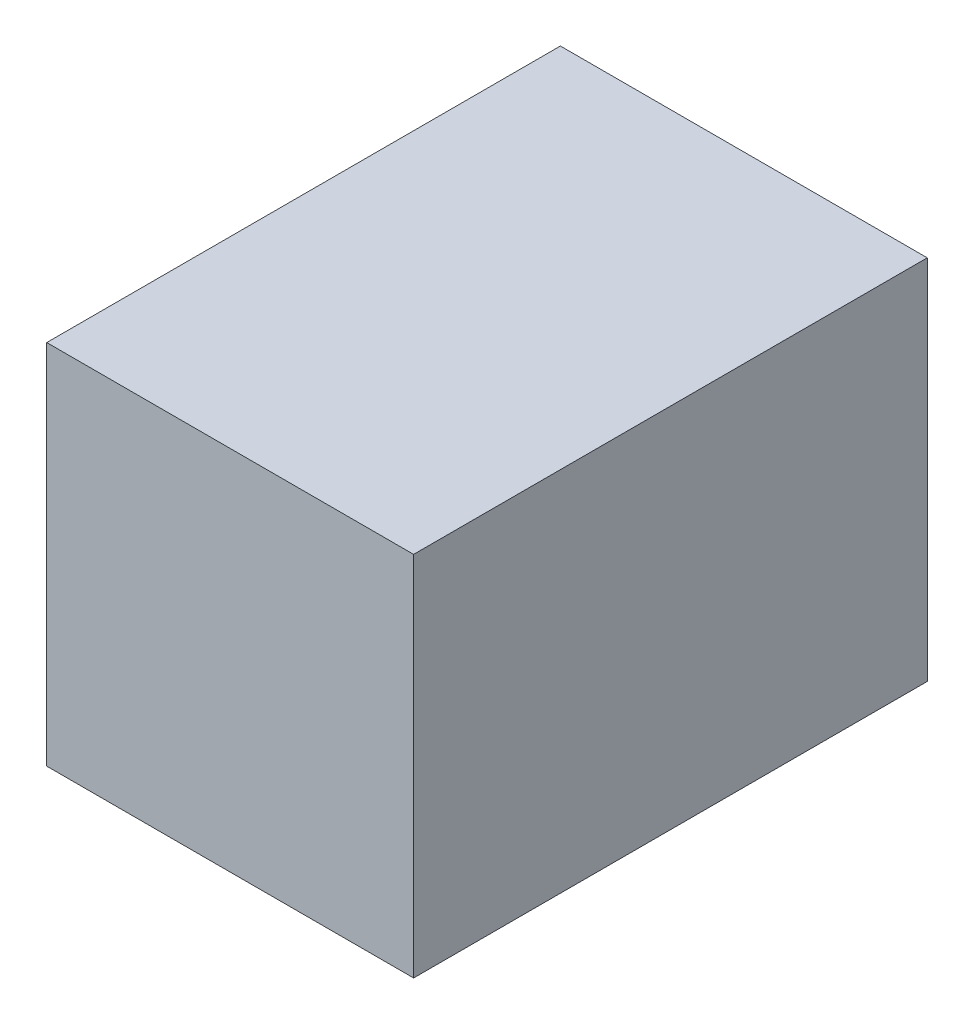
SolidWorks part; units mm, degrees
ref_plane "Front Plane" through (0, 0, 0) normal (0, 0, 1) x (1, 0, 0)
ref_plane "Top Plane" through (0, 0, 0) normal (0, 1, 0) x (1, 0, 0)
ref_plane "Right Plane" through (0, 0, 0) normal (1, 0, 0) x (0, 0, -1)
other "Configuration Table"
sketch "Sketch1" plane through (0, 0, 0) normal (0, 0, 1) x (1, 0, 0)
  line L1 (60, 900) -> (160, 900)
  line L2 (60, 900) -> (60, 1000)
  line L3 (60, 1000) -> (160, 1000)
  line L4 (160, 900) -> (160, 1000)
extrude "OVEN_yag_pompasi_24V_1" add sketch "Sketch1" against normal blind 140 from offset 640 separate body
